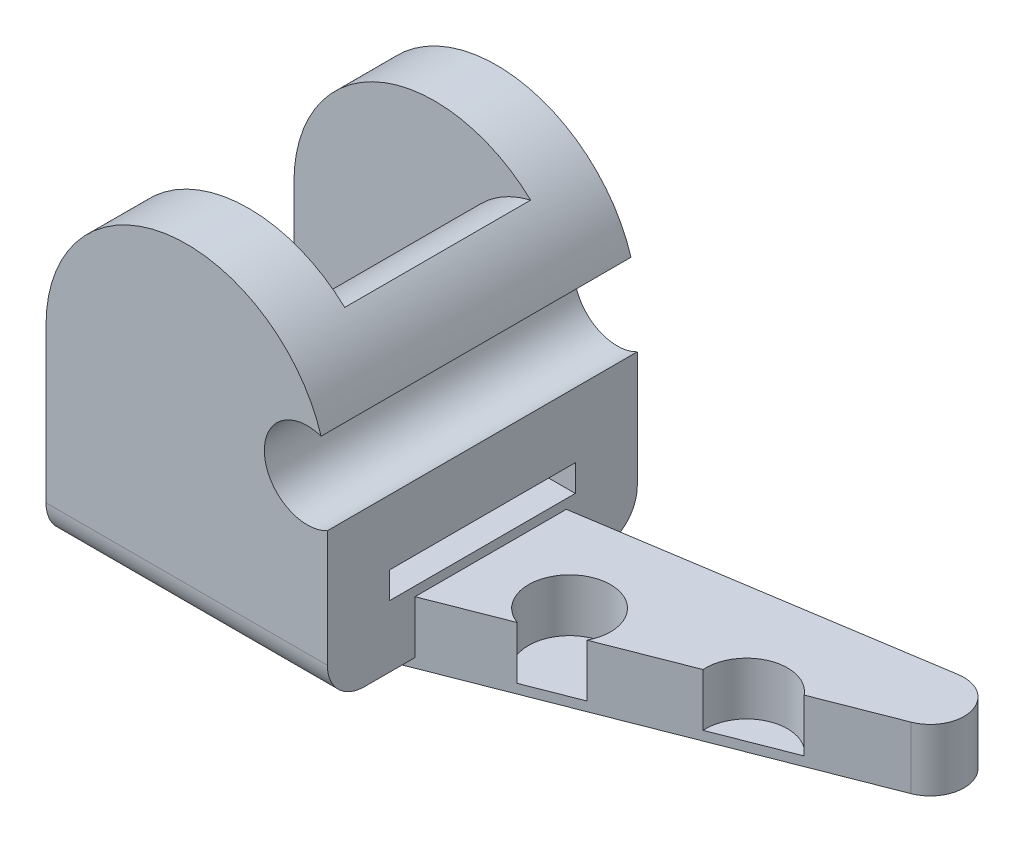
SolidWorks part; units mm, degrees
material "PW20:29:Sc:0:"
ref_plane "Front" through (0, 0, 0) normal (0, 0, 1) x (1, 0, 0)
ref_plane "Top" through (0, 0, 0) normal (0, 1, 0) x (1, 0, 0)
ref_plane "Right" through (0, 0, 0) normal (1, 0, 0) x (0, 0, -1)
sketch "Sketch4" plane through (0, 0, 0) normal (0, 0, 1) x (1, 0, 0)
  line L0 (-45.3888, 0) -> (-45.3888, -61.606)
  line L1 (-45.3888, -61.606) -> (45.3888, -61.606)
  line L2 (45.3888, -61.606) -> (45.3888, 0)
  arc A0 (45.3888, 0) -> (-45.3888, 0) centre (0, 0) ccw
extrude "\"U\" shape" add sketch "Sketch4" along normal blind 100
sketch "Sketch8" plane through (0, 0, 100) normal (0, 0, 1) x (1, 0, 0)
  circle A0 centre (38.9238, 0.2349) radius 13.8707
extrude "Inner Hole" cut sketch "Sketch8" against normal through all
shell "Thickness" thickness 20
fillet "Fillet" radius 12 2 edges at (0, -61.606, 100) (0, -61.606, 0)
ref_plane "Plane1" through (0, -64.606, 0) normal (0, -1, 0) x (1, 0, 0)
sketch "Sketch7" plane through (0, -64.606, 0) normal (0, -1, 0) x (1, 0, 0)
  line L0 (24.5188, 52.2089) -> (196.3713, 5.822) construction
  line L1 (24.5188, 26.1439) -> (154.8439, 5.822)
  line L2 (37.6343, 74.7337) -> (160.4842, 26.7179)
  line L3 (24.5188, 26.1439) -> (37.6343, 74.7337)
  arc A0 (154.8439, 5.822) -> (160.4842, 26.7179) centre (156.5212, 16.5784) ccw
extrude "Tongue" add sketch "Sketch7" against normal blind 20
sketch "Sketch9" plane through (0, -61.606, 0) normal (0, -1, 0) x (1, 0, 0)
  line L0 (-45.3888, 50) -> (169.8623, 50) construction
  line L1 (-45.3888, 80) -> (-45.3888, 20) construction
  circle A0 centre (73.5455, 50) radius 13.2198
  circle A2 centre (125.389, 44.7268) radius 13.2198
extrude "Mounting Holes" cut sketch "Sketch9" against normal through all
